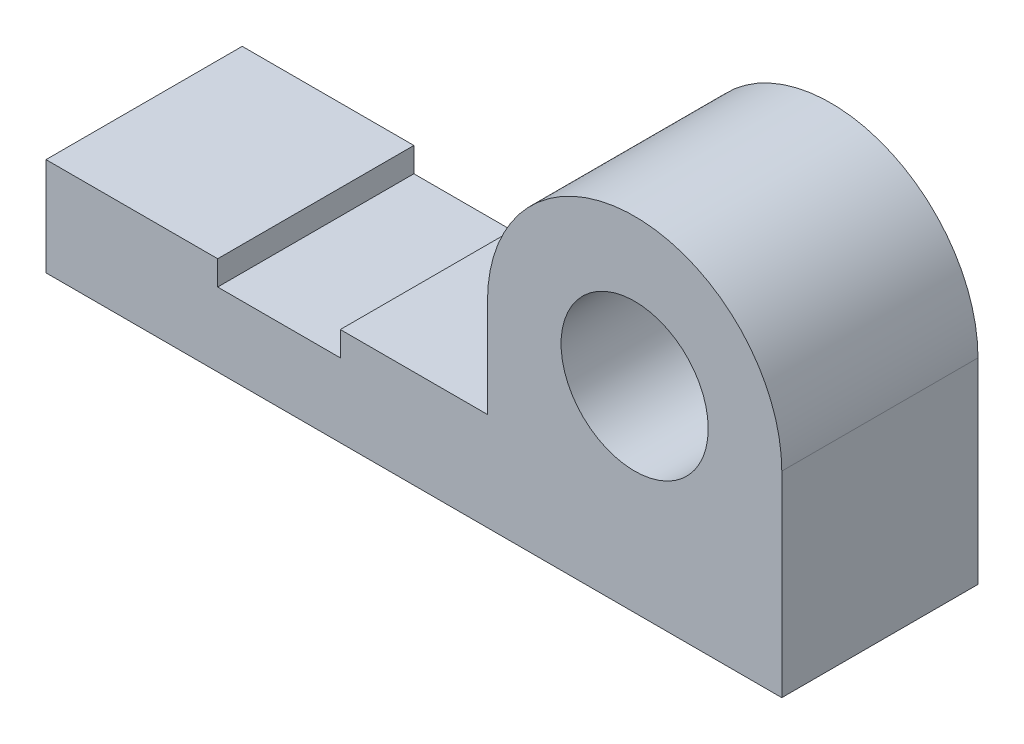
SolidWorks part; units mm, degrees
ref_plane "Front Plane" through (0, 0, 0) normal (0, 0, 1) x (1, 0, 0)
ref_plane "Top Plane" through (0, 0, 0) normal (0, 1, 0) x (1, 0, 0)
ref_plane "Right Plane" through (0, 0, 0) normal (1, 0, 0) x (0, 0, -1)
sketch "Sketch2" plane through (0, 0, 0) normal (0, 0, 1) x (1, 0, 0)
  line L0 (0, 0) -> (-150, 0)
  line L1 (-150, 0) -> (-150, 20)
  line L2 (-150, 20) -> (-115, 20)
  line L3 (-115, 20) -> (-115, 15)
  line L4 (-115, 15) -> (-90, 15)
  line L5 (-90, 15) -> (-90, 20)
  line L6 (-90, 20) -> (-60, 20)
  line L7 (-60, 20) -> (-60, 40)
  line L8 (0, 40) -> (0, 0)
  arc A0 (-60, 40) -> (0, 40) centre (-30, 40) cw
  circle A1 centre (-30, 40) radius 15
  point P13 (0, 0)
  point P14 (0, 0)
  point P15 (0, 0)
  dimension "D7" = 30
  dimension "D8" = 30
  dimension "D1" = 150
  dimension "D2" = 40
  dimension "D3" = 20
  dimension "D4" = 15
  dimension "D5" = 35
  dimension "D6" = 25
  dimension "D9" = 40
extrude "Boss-Extrude1" add sketch "Sketch2" along normal mid plane 40
